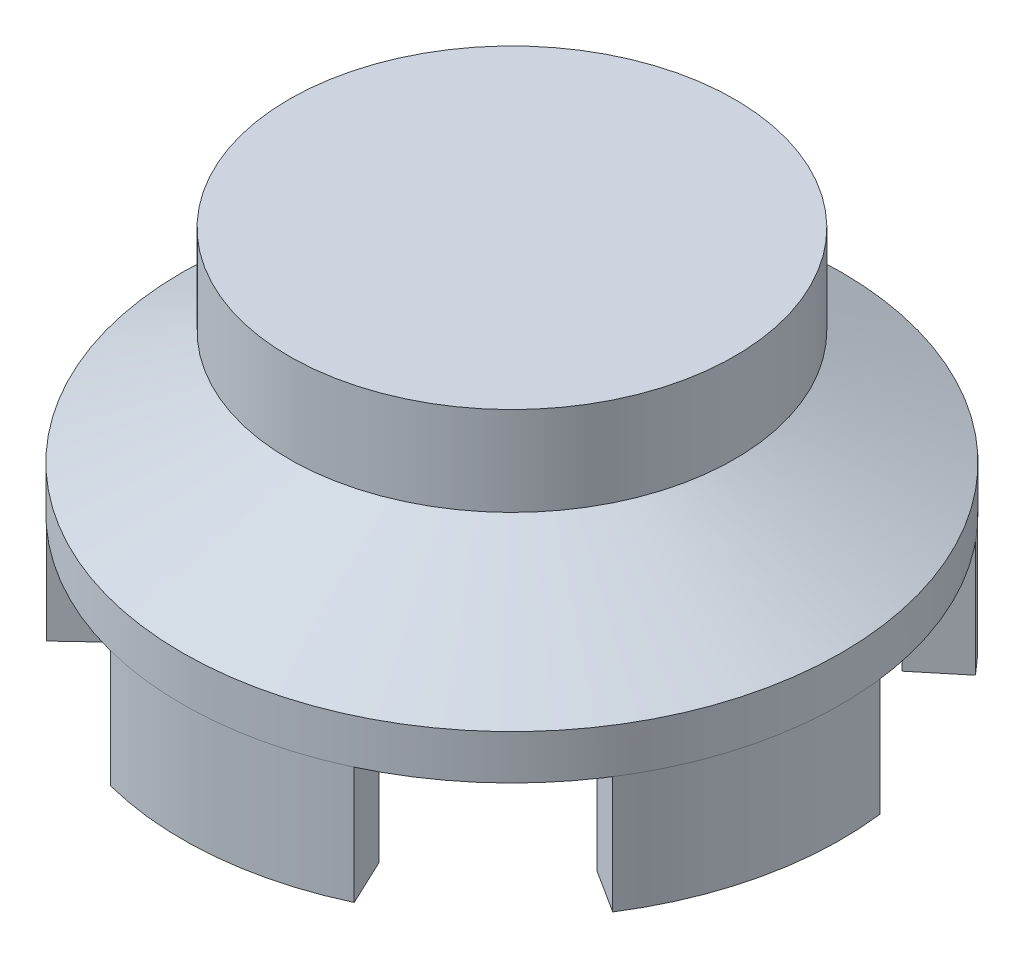
SolidWorks part; units mm, degrees
ref_plane "前基準面" through (0, 0, 0) normal (0, 0, 1) x (1, 0, 0)
ref_plane "上基準面" through (0, 0, 0) normal (0, 1, 0) x (1, 0, 0)
ref_plane "右基準面" through (0, 0, 0) normal (1, 0, 0) x (0, 0, -1)
sketch "草圖1" plane through (0, 0, 0) normal (0, 0, 1) x (1, 0, 0)
  line L0 (0, 6.1548) -> (0, 3.1548)
  line L1 (0, 3.1548) -> (4, 3.1548)
  line L2 (4, 3.1548) -> (15.5, -2.7579)
  line L3 (15.5, -2.7579) -> (18.5, -2.7579)
  line L4 (18.5, -2.7579) -> (18.5, -0.2579)
  line L5 (18.5, -0.2579) -> (4.3543, 6.1548)
  line L6 (4.3543, 6.1548) -> (0, 6.1548)
  line L7 (0, 6.1548) -> (-0.0108, 6.1944)
  dimension "D1" = 3
  dimension "D2" = 4
  dimension "D3" = 11.5
  dimension "D4" = 2.5
  dimension "D5" = 3
revolve "旋轉1" add sketch "草圖1" angle 360 about L0
sketch "草圖2" plane through (0, 3.1548, 0) normal (0, -1, 0) x (1, 0, 0)
  line L0 (0, 0) -> (0, 20.6415) construction
  line L1 (-4.6283, 17.8957) -> (-3.8968, 15.067)
  line L2 (7.8717, 16.7246) -> (6.6274, 14.081)
  line L3 (18.3385, -2.3182) -> (15.4398, -1.9518)
  line L4 (15.5895, 9.9319) -> (13.1254, 8.362)
  line L5 (3.4622, -18.1573) -> (2.9149, -15.2873)
  line L6 (14.2632, -11.7574) -> (12.0087, -9.899)
  line L7 (-16.1988, -8.9037) -> (-13.6383, -7.4963)
  line L8 (-6.7744, -17.1984) -> (-5.7036, -14.4799)
  line L9 (-13.4736, 12.6546) -> (-11.3439, 10.6543)
  line L10 (-18.45, 1.1282) -> (-15.5337, 0.9499)
  arc A0 (6.6274, 14.081) -> (-3.8968, 15.067) centre (0, 0) ccw
  arc A1 (7.8717, 16.7246) -> (-4.6283, 17.8957) centre (0, 0) ccw
  arc A2 (18.3385, -2.3182) -> (15.5895, 9.9319) centre (0, 0) ccw
  arc A3 (15.4398, -1.9518) -> (13.1254, 8.362) centre (0, 0) ccw
  arc A4 (3.4622, -18.1573) -> (14.2632, -11.7574) centre (0, 0) ccw
  arc A5 (2.9149, -15.2873) -> (12.0087, -9.899) centre (0, 0) ccw
  arc A6 (-16.1988, -8.9037) -> (-6.7744, -17.1984) centre (0, 0) ccw
  arc A7 (-13.6383, -7.4963) -> (-5.7036, -14.4799) centre (0, 0) ccw
  arc A8 (-13.4736, 12.6546) -> (-18.45, 1.1282) centre (0, 0) ccw
  arc A9 (-11.3439, 10.6543) -> (-15.5337, 0.9499) centre (0, 0) ccw
  point P26 (0, 0)
  dimension "D1" = 12.5
  dimension "D2" = 5
sketch "草圖3" plane through (0, 6.1548, 0) normal (0, 1, 0) x (1, 0, 0)
  circle A0 centre (0, 0) radius 17.5
  dimension "D1" = 35
extrude "填料-伸長3" add sketch "草圖2" along normal blind 9 from offset 3.5
sketch "草圖4" plane through (0, 6.1548, 0) normal (0, 1, 0) x (1, 0, 0)
  circle A0 centre (0, 0) radius 12.5
  dimension "D1" = 25
extrude "填料-伸長4" add sketch "草圖4" along normal blind 5
